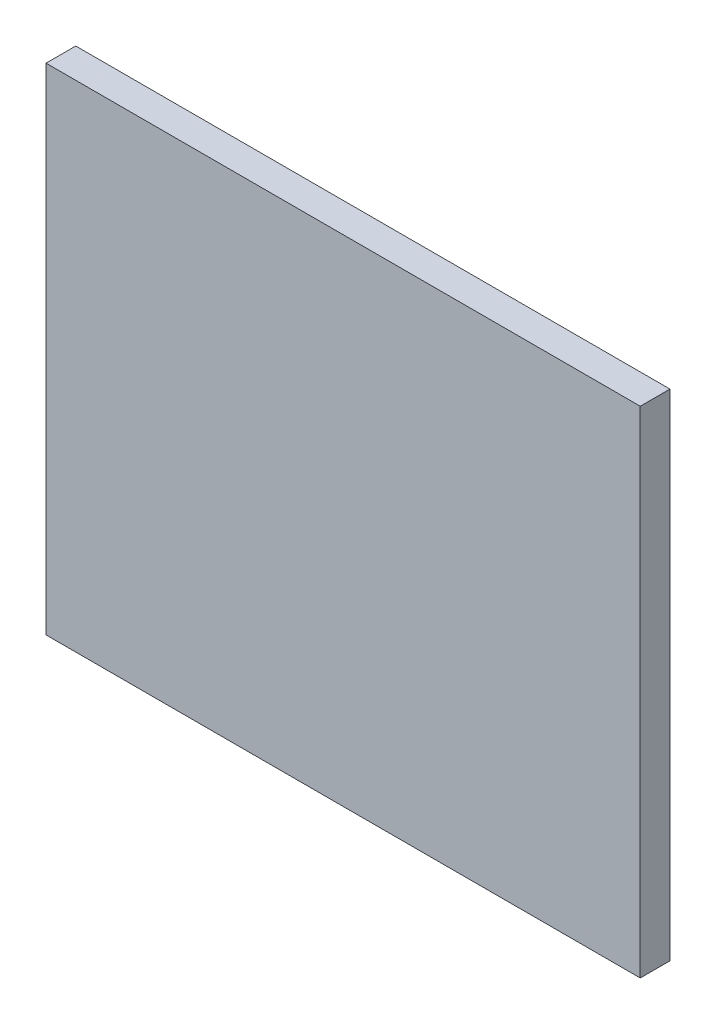
SolidWorks part; units mm, degrees
ref_plane "Front Plane" through (0, 0, 0) normal (0, 0, 1) x (1, 0, 0)
ref_plane "Top Plane" through (0, 0, 0) normal (0, 1, 0) x (1, 0, 0)
ref_plane "Right Plane" through (0, 0, 0) normal (1, 0, 0) x (0, 0, -1)
sketch "Sketch1" plane through (0, 0, 0) normal (0, 1, 0) x (1, 0, 0)
  line L1 (30, -1.5) -> (-30, -1.5)
  line L2 (30, -1.5) -> (30, 1.5)
  line L3 (30, 1.5) -> (-30, 1.5)
  line L4 (-30, -1.5) -> (-30, 1.5)
  line L5 (30, -1.5) -> (-30, 1.5) construction
  line L6 (30, 1.5) -> (-30, -1.5) construction
  point P0 (0, 0)
  dimension "D1" = 60
  dimension "D2" = 3
extrude "Boss-Extrude1" add sketch "Sketch1" along normal blind 50
